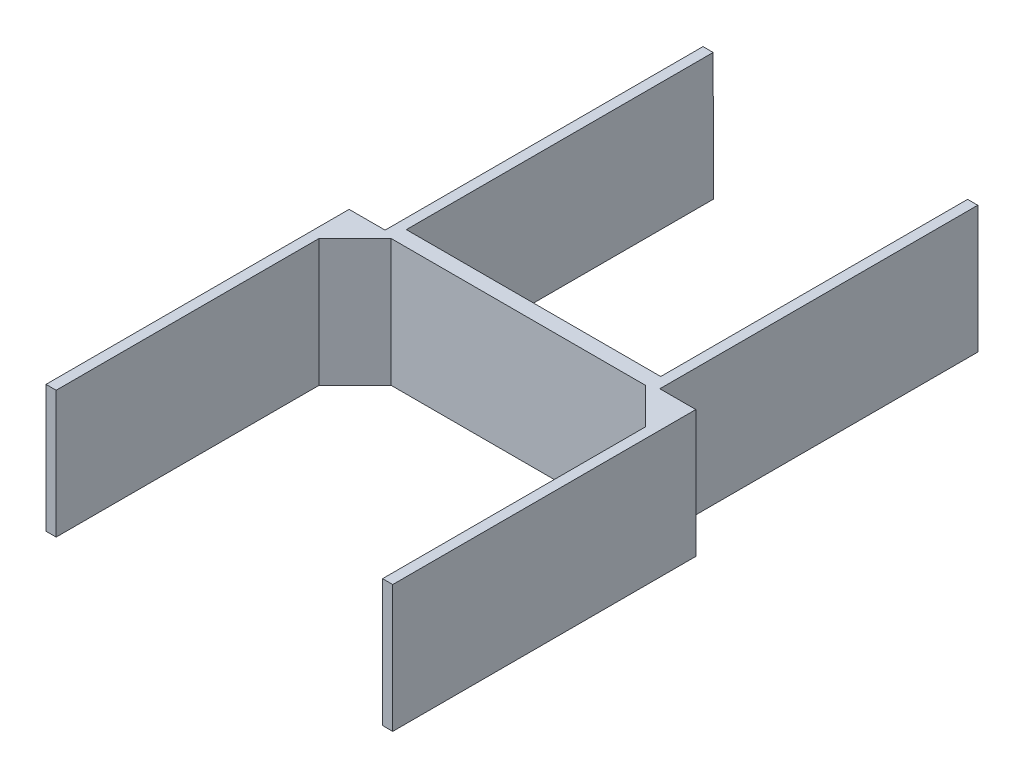
SolidWorks part; units mm, degrees
material "Plastique personnalisé"
ref_plane "Plan de face" through (0, 0, 0) normal (0, 0, 1) x (1, 0, 0)
ref_plane "Plan de dessus" through (0, 0, 0) normal (0, 1, 0) x (1, 0, 0)
ref_plane "Plan de droite" through (0, 0, 0) normal (1, 0, 0) x (0, 0, -1)
sketch "Esquisse1" plane through (0, 0, 0) normal (0, 1, 0) x (1, 0, 0)
  line L0 (-34.0711, -19.1028) -> (-34.0711, -12.0317)
  line L1 (-34.0711, -59.1028) -> (-34.0711, -19.1028)
  line L3 (-27, -12.0317) -> (-27, 37.9683)
  line L4 (-27, 37.9683) -> (-25, 37.9683)
  line L5 (-25, 37.9683) -> (-25, -9.8602)
  line L6 (-25, -12.8602) -> (-32.0711, -19.9312)
  line L7 (-32.0711, -19.9312) -> (-32.0711, -59.1028)
  line L8 (-32.0711, -59.1028) -> (-34.0711, -59.1028)
  line L9 (32.0711, -59.1028) -> (34.0711, -59.1028)
  line L10 (-25, -12.8602) -> (25, -12.8602)
  line L12 (-25, -9.8602) -> (25, -9.8602)
  line L14 (32.0711, -19.9312) -> (32.0711, -59.1028)
  line L15 (25, -12.8602) -> (32.0711, -19.9312)
  line L16 (25, 37.9683) -> (25, -9.8602)
  line L17 (27, 37.9683) -> (25, 37.9683)
  line L18 (27, -12.0317) -> (27, 37.9683)
  line L20 (34.0711, -59.1028) -> (34.0711, -19.1028)
  line L21 (-34.0711, -12.0317) -> (-27, -12.0317)
  line L22 (27, -12.0317) -> (34.0711, -12.0317)
  line L23 (34.0711, -12.0317) -> (34.0711, -19.1028)
  dimension "D1" = 135
  dimension "D2" = 40
  dimension "D3" = 10
  dimension "D5" = 2
  dimension "D6" = 2
  dimension "D8" = 50
  dimension "D10" = 3
extrude "Boss.-Extru.1" add sketch "Esquisse1" along normal blind 25 contours L12 L16 L17 L18 L22 L23 L20 L9 L14 L15 L10 L6 L7 L8 L1 L0 L21 L3 L4 L5
ref_plane "Plan1" through (34.0711, 0, 0) normal (1, 0, 0) x (0, 0, -1)
sketch "Esquisse2" plane through (34.0711, 0, 0) normal (1, 0, 0) x (0, 0, -1)
  line L0 (-59.1028, 25) -> (-71.6028, 25)
  line L1 (-71.6028, 25) -> (-71.6028, 0)
  line L2 (-71.6028, 0) -> (-59.1028, 0)
  line L4 (-59.1028, 0) -> (-12.0317, 0)
  line L5 (-12.0317, 0) -> (-12.0317, 25)
  line L6 (-12.0317, 25) -> (-59.1028, 25)
  line L7 (-59.1028, 25) -> (-59.1028, 0)
  line L8 (-59.1028, 0) -> (-12.0317, 0)
  line L10 (-12.0317, 25) -> (-59.1028, 25)
  line L15 (-12.0317, 0) -> (-12.0317, 25)
  dimension "D1" = 0
extrude "Boss.-Extru.2" add sketch "Esquisse2" against normal blind 2 contours L10 L0 L1 L2 L8 L15
ref_plane "Plan2" through (27, 0, 0) normal (1, 0, 0) x (0, 0, -1)
sketch "Esquisse3" plane through (27, 0, 0) normal (1, 0, 0) x (0, 0, -1)
  line L2 (37.9473, 25) -> (50.4473, 25)
  line L3 (50.4473, 25) -> (50.4917, 0)
  line L4 (50.4917, 0) -> (37.9473, 0)
  line L5 (37.9473, 25) -> (37.9473, 0)
  point P0 (38.0492, 0.078)
  dimension "D1" = 12.5
extrude "Boss.-Extru.3" add sketch "Esquisse3" against normal blind 2
ref_plane "Plan3" through (-34.0711, 0, 0) normal (-1, 0, 0) x (0, 0, 1)
sketch "Esquisse4" plane through (-34.0711, 0, 0) normal (-1, 0, 0) x (0, 0, 1)
  line L1 (59.1028, 24.5046) -> (59.1028, 0)
  line L2 (59.1028, 25) -> (59.1028, 0)
  line L3 (59.1028, 25) -> (71.6028, 25)
  line L4 (71.6028, 25) -> (71.6028, 0)
  line L5 (71.6028, 0) -> (59.1028, 0)
  dimension "D1" = 12.5
ref_plane "Plan4" through (-27, 0, 0) normal (-1, 0, 0) x (0, 0, 1)
sketch "Esquisse5" plane through (-27, 0, 0) normal (-1, 0, 0) x (0, 0, 1)
  line L1 (-37.9683, 0) -> (-37.9683, 25)
  line L2 (-37.9683, 25) -> (-50.4473, 25)
  line L3 (-50.4473, 25) -> (-50.4917, 0)
  line L4 (-50.4917, 0) -> (-37.9683, 0)
extrude "Boss.-Extru.5" add sketch "Esquisse5" against normal blind 2 contours L1 L2 L3 L4
ref_plane "Plan8" through (25, 0, 0) normal (-1, 0, 0) x (0, 0, 1)
extrude "Boss.-Extru.6" add sketch "Esquisse4" against normal blind 2 contours L2 L3 L4 L5
